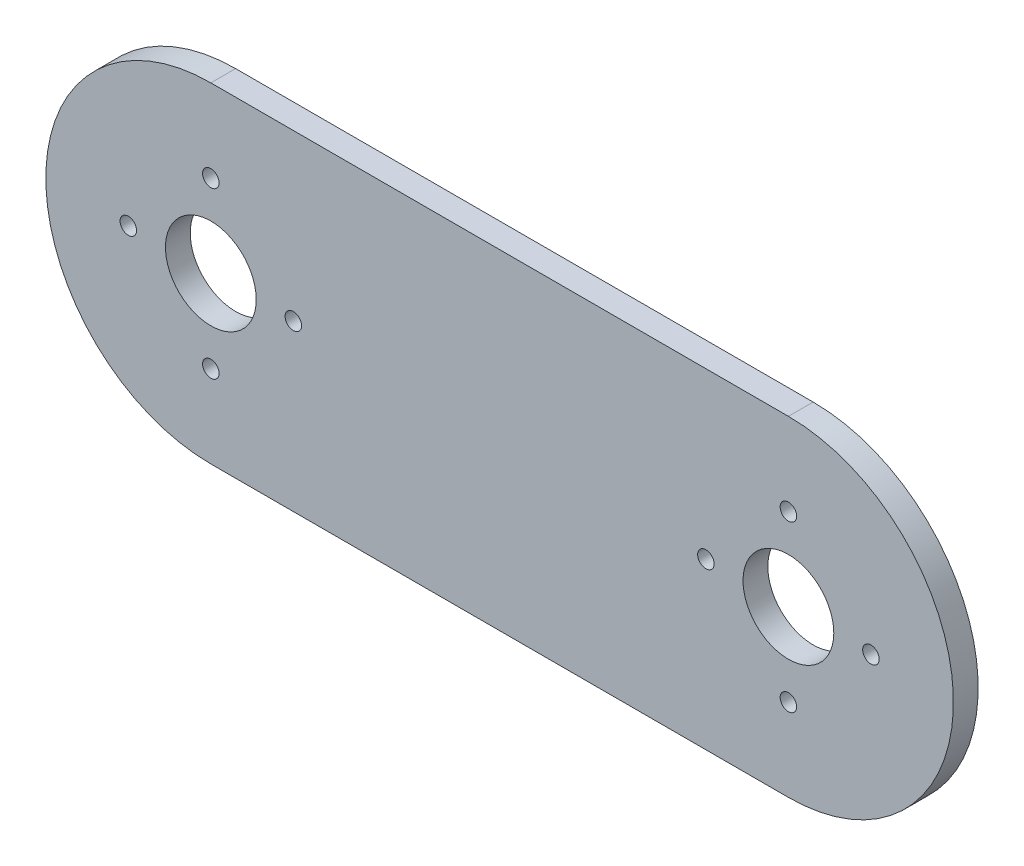
SolidWorks part; units mm, degrees
material "Acrylic (Medium-high impact)"
ref_plane "Front Plane" through (0, 0, 0) normal (0, 0, 1) x (1, 0, 0)
ref_plane "Top Plane" through (0, 0, 0) normal (0, 1, 0) x (1, 0, 0)
ref_plane "Right Plane" through (0, 0, 0) normal (1, 0, 0) x (0, 0, -1)
sketch "Sketch1" plane through (0, 0, 0) normal (0, 0, 1) x (1, 0, 0)
  line L0 (0, 0) -> (70, 0) construction
  line L1 (0, 20) -> (70, 20)
  line L2 (0, -20) -> (70, -20)
  line L3 (-1000, 0) -> (49000, 0) construction
  line L4 (0, -1000) -> (0, 49000) construction
  line L5 (70, -1000) -> (70, 49000) construction
  arc A0 (0, 20) -> (0, -20) centre (0, 0) ccw
  arc A1 (70, -20) -> (70, 20) centre (70, 0) ccw
  circle A2 centre (0, 0) radius 10 construction
  circle A3 centre (70, 0) radius 10 construction
  circle A4 centre (10, 0) radius 1
  circle A5 centre (0, -10) radius 1
  circle A6 centre (-10, 0) radius 1
  circle A7 centre (0, 10) radius 1
  circle A8 centre (80, 0) radius 1
  circle A9 centre (60, 0) radius 1
  circle A10 centre (70, 10) radius 1
  circle A11 centre (70, -10) radius 1
  circle A12 centre (0, 0) radius 5.5
  circle A13 centre (70, 0) radius 5.5
  point P3 (35, 0)
  point P29 (0, 0)
  dimension "D1" = 4
  dimension "D2" = 70
  dimension "D4" = 2
  dimension "D5" = 2
  dimension "D6" = 2
  dimension "D7" = 2
  dimension "D8" = 2
  dimension "D9" = 20
  dimension "D10" = 20
  dimension "D11" = 20
  dimension "D3" = 40
  dimension "D12" = 0
  dimension "D13" = 10
extrude "Boss-Extrude1" add sketch "Sketch1" along normal blind 3
